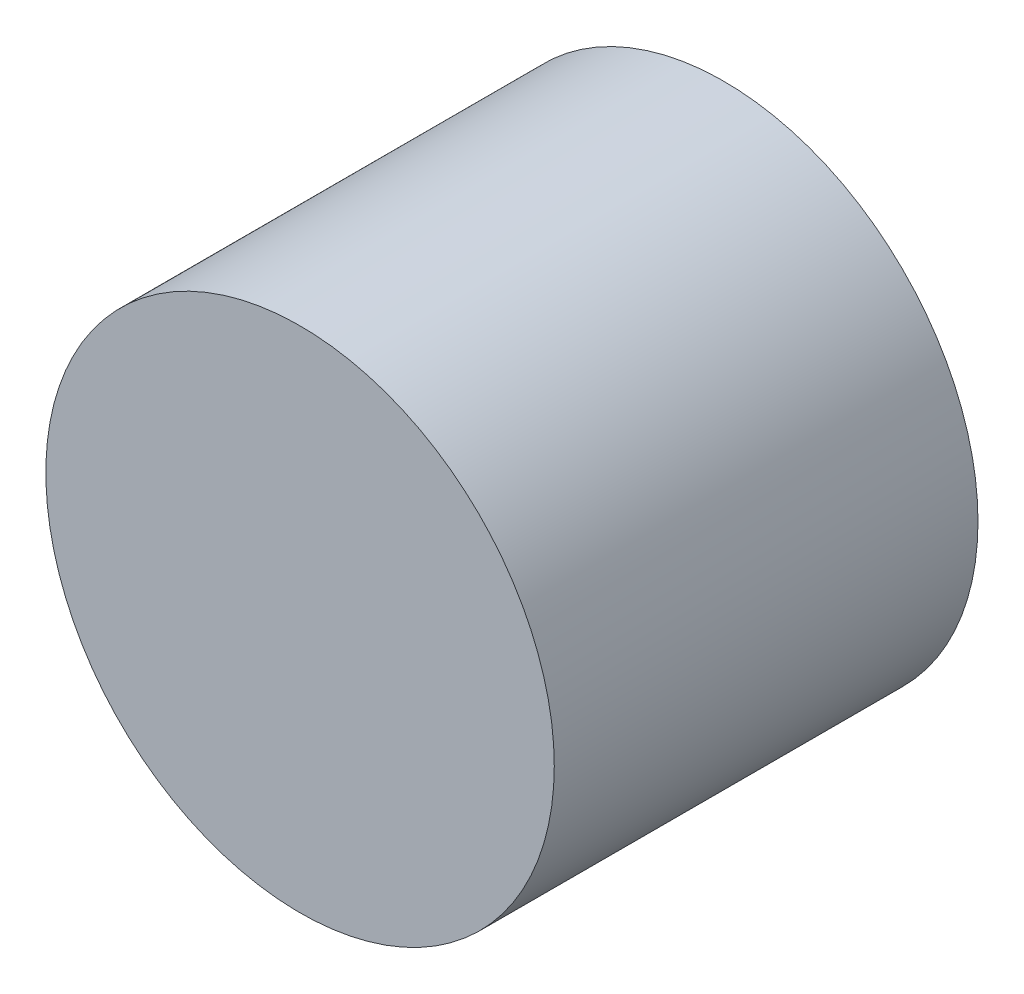
SolidWorks part; units mm, degrees
material "Custom Plastic"
ref_plane "Front Plane" through (0, 0, 0) normal (0, 0, 1) x (1, 0, 0)
ref_plane "Top Plane" through (0, 0, 0) normal (0, 1, 0) x (1, 0, 0)
ref_plane "Right Plane" through (0, 0, 0) normal (1, 0, 0) x (0, 0, -1)
sketch "Sketch1" plane through (0, 0, 0) normal (0, 0, 1) x (1, 0, 0)
  circle A0 centre (0, 0) radius 4.5
extrude "Boss-Extrude1" add sketch "Sketch1" along normal blind 7.5
